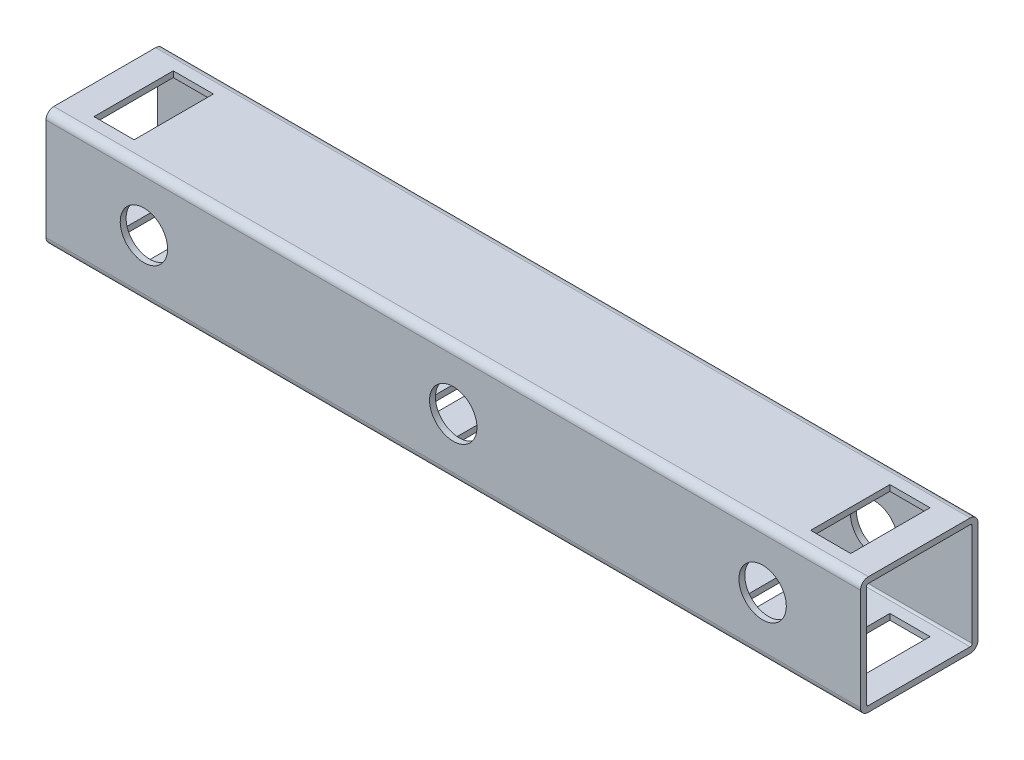
SolidWorks part; units mm, degrees
material "AISI 304"
ref_plane "Спереди" through (0, 0, 0) normal (0, 0, 1) x (1, 0, 0)
ref_plane "Сверху" through (0, 0, 0) normal (0, 1, 0) x (1, 0, 0)
ref_plane "Справа" through (0, 0, 0) normal (1, 0, 0) x (0, 0, -1)
other "Configuration Table"
sketch "Эскиз1" plane through (0, 0, 0) normal (1, 0, 0) x (0, 0, -1)
  line L0 (-26, 27) -> (26, 27)
  line L1 (-26, -30) -> (26, -30)
  line L2 (-30, -26) -> (-30, 26)
  line L3 (-26, 30) -> (26, 30)
  line L4 (30, -26) -> (30, 26)
  line L5 (-30, -30) -> (30, 30) construction
  line L6 (-30, 30) -> (30, -30) construction
  line L7 (27, -26) -> (27, 26)
  line L8 (-26, -27) -> (26, -27)
  line L9 (-27, -26) -> (-27, 26)
  arc A0 (-26, -30) -> (-30, -26) centre (-26, -26) cw
  arc A1 (26, -30) -> (30, -26) centre (26, -26) ccw
  arc A2 (26, 30) -> (30, 26) centre (26, 26) cw
  arc A3 (-30, 26) -> (-26, 30) centre (-26, 26) cw
  arc A4 (26, 27) -> (27, 26) centre (26, 26) cw
  arc A5 (26, -27) -> (27, -26) centre (26, -26) ccw
  arc A6 (-26, -27) -> (-27, -26) centre (-26, -26) cw
  arc A7 (-27, 26) -> (-26, 27) centre (-26, 26) cw
  point P0 (0, 0)
  dimension "D3" = 4
  dimension "D5" = 1
  dimension "D1" = 60
  dimension "D2" = 60
  dimension "D4" = 3
extrude "Бобышка-Вытянуть1" add sketch "Эскиз1" along normal mid plane 416
sketch "Эскиз3" plane through (0, -30, 0) normal (0, -1, 0) x (1, 0, 0)
  line L0 (-12, -1) -> (-12, 0) construction
  line L1 (-16, -16) -> (-8, -16)
  line L2 (-16, -16) -> (-16, 14)
  line L3 (-16, 14) -> (-8, 14)
  line L4 (-8, -16) -> (-8, 14)
  line L5 (-16, -16) -> (-8, 14) construction
  line L6 (-16, 14) -> (-8, -16) construction
  point P0 (-12, -1)
  point P8 (0, 0)
  dimension "D1" = 8
  dimension "D2" = 30
  dimension "D3" = 1
  dimension "D4" = 12
extrude "Вырез-Вытянуть1" cut sketch "Эскиз3" against normal up to surface (3 mm away) up to face at (0, -27, 0)
pattern_linear "Линейный массив1" count 6 spacing 24 along (-1, 0, 0) count 7 spacing 24 along (1, 0, 0) of "Вырез-Вытянуть1"
sketch "Эскиз5" plane through (0, -30, 0) normal (0, -1, 0) x (1, 0, 0)
  line L0 (0, 0) -> (0, 59.1078) construction
  line L1 (-183, -10) -> (-183, 10) construction
  line L4 (-193.25, -10) -> (-193.25, 10) construction
  line L8 (-193.25, -20.25) -> (-172.75, -20.25)
  line L9 (-193.25, -20.25) -> (-193.25, 20.25)
  line L10 (-172.75, -10) -> (-172.75, 10) construction
  line L11 (183, -10) -> (183, 10) construction
  line L12 (193.25, -10) -> (193.25, 10) construction
  line L13 (172.75, -10) -> (172.75, 10) construction
  line L14 (-208, 26) -> (-208, -26) construction
  line L15 (-183, 0) -> (183, 0) construction
  line L16 (-193.25, 20.25) -> (-172.75, 20.25)
  line L17 (-172.75, -20.25) -> (-172.75, 20.25)
  line L18 (-193.25, -20.25) -> (-172.75, 20.25) construction
  line L19 (-193.25, 20.25) -> (-172.75, -20.25) construction
  line L20 (172.75, -20.25) -> (193.25, -20.25)
  line L21 (172.75, -20.25) -> (172.75, 20.25)
  line L22 (172.75, 20.25) -> (193.25, 20.25)
  line L23 (193.25, -20.25) -> (193.25, 20.25)
  line L24 (172.75, -20.25) -> (193.25, 20.25) construction
  line L25 (172.75, 20.25) -> (193.25, -20.25) construction
  arc A4 (-193.25, -10) -> (-172.75, -10) centre (-183, -10) ccw construction
  arc A5 (-172.75, 10) -> (-193.25, 10) centre (-183, 10) ccw construction
  arc A6 (193.25, -10) -> (172.75, -10) centre (183, -10) cw construction
  arc A7 (172.75, 10) -> (193.25, 10) centre (183, 10) cw construction
  point P5 (-183, 0)
  point P13 (183, 0)
  dimension "D3" = 40.5
  dimension "D1" = 20.5
  dimension "D2" = 25
  dimension "D4" = 20.5
  dimension "D5" = 40.5
extrude "Вырез-Вытянуть2" cut sketch "Эскиз5" against normal up to surface (60 mm away) up to face at (0, 30, 0)
sketch "Эскиз6" plane through (0, -30, 0) normal (0, -1, 0) x (1, 0, 0)
  line L0 (208, 26) -> (208, -26) construction
  line L1 (-152, -122.9818) -> (152, -122.9818)
  line L2 (-152, -122.9818) -> (-152, 122.9818)
  line L3 (-152, 122.9818) -> (152, 122.9818)
  line L4 (152, -122.9818) -> (152, 122.9818)
  line L5 (-152, -122.9818) -> (152, 122.9818) construction
  line L6 (-152, 122.9818) -> (152, -122.9818) construction
  point P0 (0, 0)
  dimension "D1" = 56
split line "Разделяющая линия1"
sketch "Эскиз10" plane through (0, 0, -30) normal (0, 0, -1) x (-1, 0, 0)
  line L0 (0, 0) -> (0, 67.7802) construction
  line L1 (-208, -26) -> (-208, 26) construction
  line L8 (-208, -17) -> (208, -17) construction
  line L9 (208, -26) -> (208, 26) construction
  line L10 (-152, -30) -> (152, -30) construction
  line L11 (-158, 0) -> (0, 0) construction
  circle A0 centre (-158, 0) radius 12.1
  circle A1 centre (158, 0) radius 12.1
  circle A2 centre (0, 0) radius 12.1
  dimension "D1" = 50
  dimension "D2" = 24.2
  dimension "D3" = 30
  dimension "D4" = 13
extrude "Вырез-Вытянуть5" cut sketch "Эскиз10" against normal up to surface (60 mm away) up to face at (0, 0, 30)
